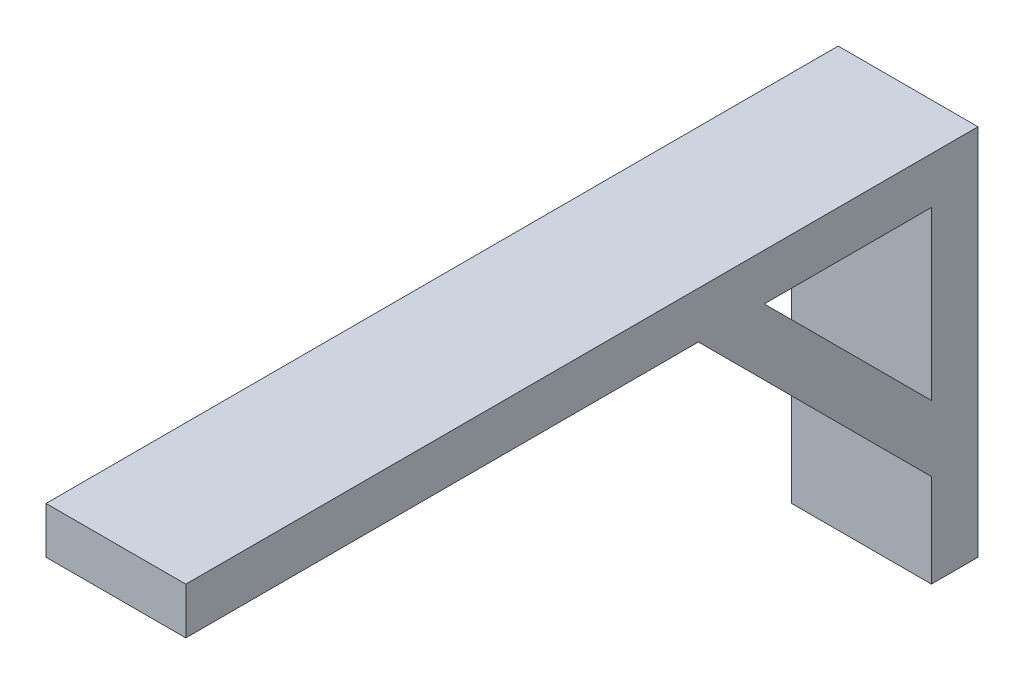
SolidWorks part; units mm, degrees
ref_plane "Front Plane" through (0, 0, 0) normal (0, 0, 1) x (1, 0, 0)
ref_plane "Top Plane" through (0, 0, 0) normal (0, 1, 0) x (1, 0, 0)
ref_plane "Right Plane" through (0, 0, 0) normal (1, 0, 0) x (0, 0, -1)
sketch "Sketch1" plane through (0, 0, 0) normal (1, 0, 0) x (0, 0, -1)
  line L0 (0, 0) -> (0, 203.2)
  line L1 (0, 203.2) -> (-431.8, 203.2)
  line L2 (-431.8, 203.2) -> (-431.8, 177.8)
  line L3 (-431.8, 177.8) -> (-152.4, 177.8)
  line L4 (-152.4, 177.8) -> (-25.4, 50.8)
  line L5 (-25.4, 50.8) -> (-25.4, 0)
  line L6 (-25.4, 0) -> (0, 0)
  line L7 (-116.479, 177.8) -> (-25.4, 177.8)
  line L8 (-25.4, 177.8) -> (-25.4, 86.721)
  line L9 (-25.4, 86.721) -> (-116.479, 177.8)
  dimension "D1" = 25.4
  dimension "D2" = 25.4
  dimension "D3" = 203.2
  dimension "D4" = 431.8
  dimension "D5" = 135
  dimension "D6" = 50.8
  dimension "D7" = 25.4
extrude "Boss-Extrude1" add sketch "Sketch1" along normal blind 76.2
equation "\"Support_Width\"= 1in"
equation "\"D1@Sketch1\"=\"Support_Width\""
equation "\"D2@Sketch1\"=\"Support_Width\""
equation "\"D7@Sketch1\"=\"Support_Width\""
equation "\"D6@Sketch1\"=\"D3@Sketch1\"-6"
